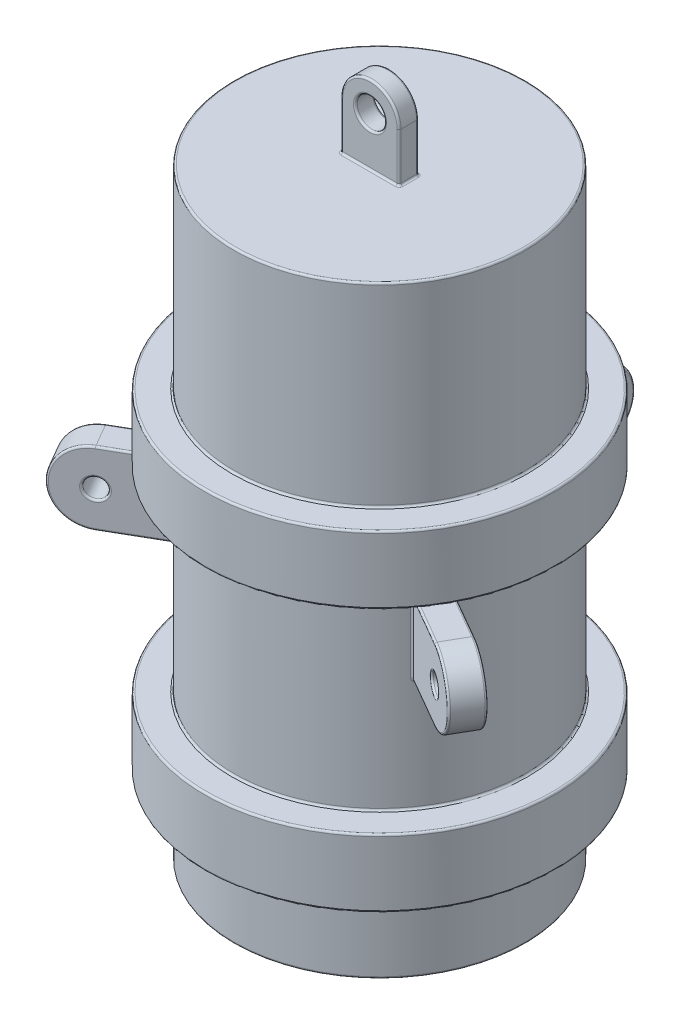
SolidWorks part; units mm, degrees
ref_plane "Alzado" through (0, 0, 0) normal (0, 0, 1) x (1, 0, 0)
ref_plane "Planta" through (0, 0, 0) normal (0, 1, 0) x (1, 0, 0)
ref_plane "Vista lateral" through (0, 0, 0) normal (1, 0, 0) x (0, 0, -1)
sketch "Croquis1" plane through (0, 0, 0) normal (0, 0, 1) x (1, 0, 0)
  line L0 (0, 0) -> (0, 62) construction
  line L1 (-4, 0) -> (-15, 0)
  line L2 (-15, 0) -> (-15, 8)
  line L3 (-15, 8) -> (-18, 8)
  line L4 (-18, 8) -> (-18, 15)
  line L5 (-18, 15) -> (-15, 15)
  line L6 (-15, 15) -> (-15, 35)
  line L7 (-15, 35) -> (-18, 35)
  line L8 (-18, 35) -> (-18, 42)
  line L9 (-18, 42) -> (-15, 42)
  line L10 (-15, 42) -> (-15, 62)
  line L11 (-15, 62) -> (0, 62)
  line L12 (-4, 1) -> (-14, 1)
  line L13 (-14, 1) -> (-14, 9)
  line L14 (-14, 9) -> (-17, 9)
  line L15 (-17, 9) -> (-17, 14)
  line L16 (-17, 14) -> (-14, 14)
  line L17 (-14, 14) -> (-14, 36)
  line L18 (-14, 36) -> (-17, 36)
  line L19 (-17, 36) -> (-17, 41)
  line L20 (-17, 41) -> (-14, 41)
  line L21 (-14, 41) -> (-14, 61)
  line L22 (-14, 61) -> (0, 61)
  line L23 (-4, 1) -> (-4, 0)
  line L24 (0, 62) -> (0, 61)
  dimension "D1" = 4
  dimension "D2" = 11
  dimension "D3" = 8
  dimension "D4" = 7
  dimension "D5" = 20
  dimension "D6" = 20
  dimension "D7" = 7
  dimension "D8" = 3
  dimension "D9" = 1
revolve "Revolución1" add sketch "Croquis1" angle 360 about L0
sketch "Croquis2" plane through (0, 0, 0) normal (0, 0, 1) x (1, 0, 0)
  line L0 (15, 62) -> (-15, 62) construction
  line L1 (-3, 62) -> (3, 62)
  line L2 (-3, 62) -> (-3, 67)
  line L4 (3, 67) -> (3, 62)
  circle A0 centre (0, 67) radius 1.5
  arc A1 (-3, 67) -> (3, 67) centre (0, 67) cw
  point P7 (0, 62)
  dimension "D1" = 3
  dimension "D3" = 1.5
  dimension "D2" = 5
extrude "Saliente-Extruir1" add sketch "Croquis2" along normal mid plane 2
sketch "Croquis3" plane through (0, 0, 0) normal (1, 0, 0) x (0, 0, -1)
  line L0 (14, 34) -> (21, 34)
  line L1 (14, 14) -> (14, 36) construction
  line L3 (21, 26.5) -> (14, 26.5)
  line L4 (14, 26.5) -> (14, 34)
  line L5 (-18, 35) -> (18, 35) construction
  circle A0 centre (21, 30.25) radius 1
  arc A1 (21, 34) -> (21, 26.5) centre (21, 30.25) cw
  point P12 (14, 30.25)
  dimension "D4" = 2
  dimension "D1" = 7
  dimension "D2" = 1
  dimension "D3" = 7.5
extrude "Saliente-Extruir2" add sketch "Croquis3" along normal mid plane 3
pattern_circular "MatrizC1" count 3 over 360 about axis through (0, 0, 0) along (0, 1, 0) of "Saliente-Extruir2"
fillet "Redondeo1" radius 0.2 70 edges at (19.8026, 30.25, 9.701) (18.3026, 30.25, 12.299) (16.3059, 26.5, 7.6822) (22.1841, 30.25, 11.076) (16.3059, 34, 7.6822) (14.8059, 26.5, 10.2802) (20.6841, 30.25, 13.674) (14.8059, 34, 10.2802) (12.9904, 34, 7.5) (12.9904, 26.5, 7.5) (-18.3026, 30.25, 12.299) (-19.8026, 30.25, 9.701) (-14.8059, 26.5, 10.2802) (-20.6841, 30.25, 13.674) (-14.8059, 34, 10.2802) (-16.3059, 26.5, 7.6822) (-22.1841, 30.25, 11.076) (-16.3059, 34, 7.6822) (-12.9904, 34, 7.5) (-12.9904, 26.5, 7.5) (-1.5, 30.25, -22) (1.5, 30.25, -22) (-1.5, 26.5, -17.9624) (-1.5, 30.25, -24.75) (-1.5, 34, -17.9624) (1.5, 26.5, -17.9624) (1.5, 30.25, -24.75) (1.5, 34, -17.9624) (0, 34, -15) (0, 26.5, -15) (1.5, 67, -1) (1.5, 67, 1) (-3, 64.5, -1) (0, 62, -1) (3, 64.5, -1) (0, 70, -1) (-3, 64.5, 1) (0, 62, 1) (3, 64.5, 1) (0, 70, 1) (3, 62, 0) (-3, 62, 0) (0, 61, -14) (0, 41, -14) (0, 41, -17) (0, 36, -17) (0, 36, -14) (0, 14, -14) (0, 14, -17) (0, 9, -17) (0, 9, -14) (0, 1, -14) (0, 1, -4) (0, 0, -4) (0, 0, -15) (0, 8, -15) (0, 8, -18) (0, 15, -18) (0, 15, -15) (0, 35, -15) (0, 35, -18) (0, 42, -18) (0, 42, -15) (-1.5, 30.25, -14.9248) (1.5, 30.25, -14.9248) (-12.1753, 30.25, 8.7614) (-13.6753, 30.25, 6.1634) (13.6753, 30.25, 6.1634) (12.1753, 30.25, 8.7614) (0, 62, -15)
